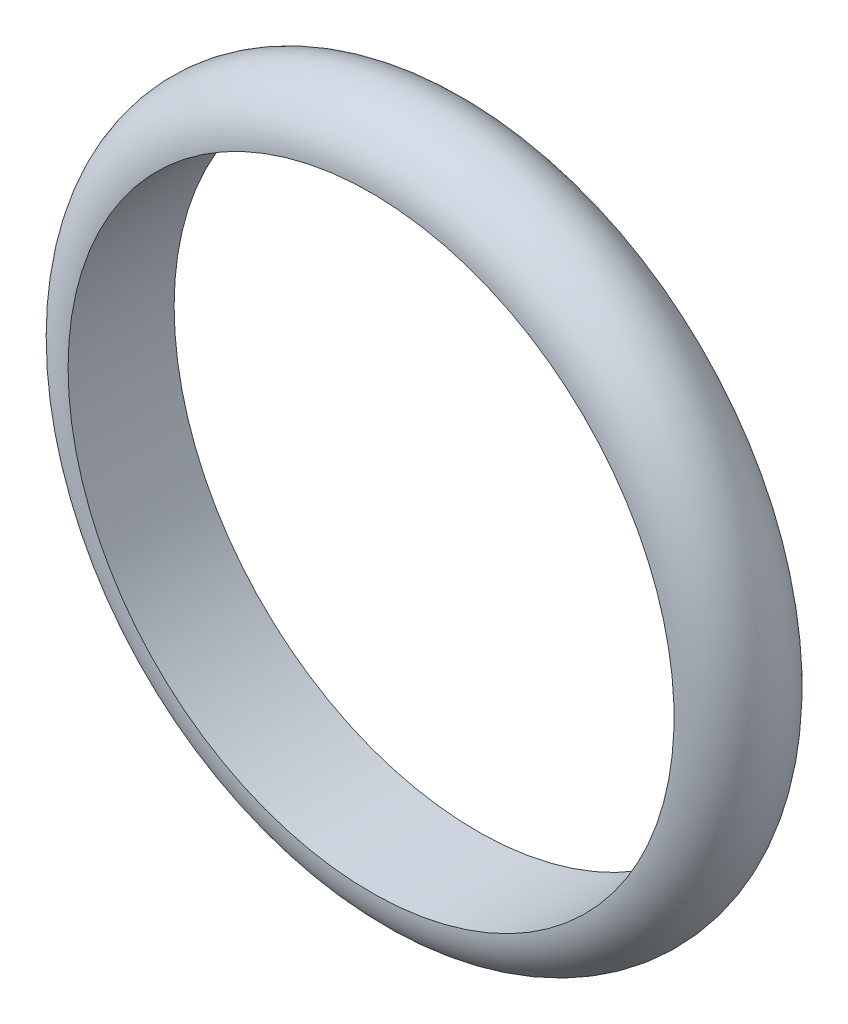
SolidWorks part; units mm, degrees
ref_plane "前视基准面" through (0, 0, 0) normal (0, 0, 1) x (1, 0, 0)
ref_plane "上视基准面" through (0, 0, 0) normal (0, 1, 0) x (1, 0, 0)
ref_plane "右视基准面" through (0, 0, 0) normal (1, 0, 0) x (0, 0, -1)
sketch "草图1" plane through (0, 0, 0) normal (0, 0, 1) x (1, 0, 0)
  circle A0 centre (0, 0) radius 25
extrude "凸台-拉伸1" add sketch "草图1" along normal blind 7
sketch "草图2" plane through (0, 0, 7) normal (0, 0, 1) x (1, 0, 0)
  circle A0 centre (0, 0) radius 20
extrude "切除-拉伸1" cut sketch "草图2" against normal blind 31
sketch "草图3" plane through (0, 0, 7) normal (0, 0, 1) x (1, 0, 0)
  line L0 (0, 25) -> (0, -25)
  circle A0 centre (0, 0) radius 25 construction
ref_plane "基准面1" through (0, 0, 0) normal (-1, 0, 0) x (0, -1, 0)
sketch "草图6" plane through (0, 0, 0) normal (-1, 0, 0) x (0, -1, 0)
  line L0 (0, 0) -> (0, 7)
  line L1 (-25, 7) -> (25, 7) construction
sketch "草图7" plane through (0, 0, 0) normal (-1, 0, 0) x (0, -1, 0)
  line L12 (-25, 7) -> (25, 7) construction
  line L15 (-20, 7) -> (-25, 7)
  line L16 (-25, 7) -> (-25, 0)
  line L17 (-25, 0) -> (-20, 0)
  arc A5 (-20, 7) -> (-20, 0) centre (-20, 3.5) ccw
revolve "切除-旋转1" cut sketch "草图7" angle 360 about L0
scale "缩放比例1" scale about centroid uniform scaling yes scale factor 1.5
